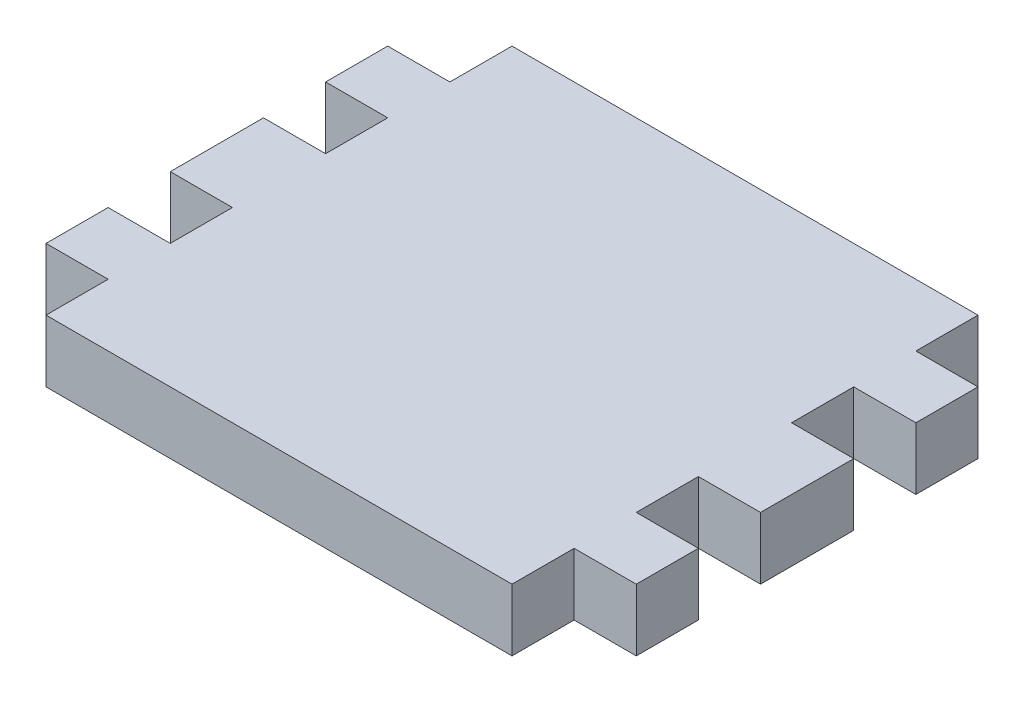
SolidWorks part; units mm, degrees
ref_plane "Front Plane" through (0, 0, 0) normal (0, 0, 1) x (1, 0, 0)
ref_plane "Top Plane" through (0, 0, 0) normal (0, 1, 0) x (1, 0, 0)
ref_plane "Right Plane" through (0, 0, 0) normal (1, 0, 0) x (0, 0, -1)
sketch "Sketch1" plane through (0, 0, 0) normal (0, 1, 0) x (1, 0, 0)
  line L1 (-17.8026, 11.0462) -> (30.4574, 11.0462)
  line L2 (-17.8026, 11.0462) -> (-17.8026, -27.0538)
  line L3 (-17.8026, -27.0538) -> (30.4574, -27.0538)
  line L4 (30.4574, 11.0462) -> (30.4574, -27.0538)
  dimension "D1" = 48.26
  dimension "D2" = 38.1
extrude "Boss-Extrude1" add sketch "Sketch1" along normal blind 5.08
sketch "Sketch2" plane through (0, 5.08, 0) normal (0, 1, 0) x (1, 0, 0)
  line L0 (25.3774, -27.0538) -> (25.3774, -21.9738)
  line L1 (-12.7226, 11.0462) -> (-12.7226, -27.0538) construction
  line L2 (30.4574, 11.0462) -> (-17.8026, 11.0462) construction
  line L3 (-17.8026, -27.0538) -> (30.4574, -27.0538) construction
  line L4 (6.3274, 11.0462) -> (6.3274, -27.0538) construction
  line L5 (-17.8026, 11.0462) -> (-17.8026, -27.0538) construction
  line L6 (25.3774, -16.8938) -> (25.3774, -11.8138)
  line L7 (-17.8026, 11.0462) -> (-12.7226, 11.0462)
  line L8 (-17.8026, 11.0462) -> (-17.8026, 5.9662)
  line L9 (-17.8026, 5.9662) -> (-12.7226, 5.9662)
  line L10 (-12.7226, 11.0462) -> (-12.7226, 5.9662)
  line L11 (-17.8026, 0.8862) -> (-12.7226, 0.8862)
  line L12 (-17.8026, 0.8862) -> (-17.8026, -4.1938)
  line L13 (-17.8026, -4.1938) -> (-12.7226, -4.1938)
  line L14 (-12.7226, 0.8862) -> (-12.7226, -4.1938)
  line L15 (-17.8026, -27.0538) -> (-12.7226, -27.0538)
  line L16 (-17.8026, -27.0538) -> (-17.8026, -21.9738)
  line L17 (-17.8026, -21.9738) -> (-12.7226, -21.9738)
  line L18 (-12.7226, -27.0538) -> (-12.7226, -21.9738)
  line L19 (-17.8026, -16.8938) -> (-12.7226, -16.8938)
  line L20 (-17.8026, -16.8938) -> (-17.8026, -11.8138)
  line L21 (-17.8026, -11.8138) -> (-12.7226, -11.8138)
  line L22 (-12.7226, -16.8938) -> (-12.7226, -11.8138)
  line L23 (25.3774, 0.8862) -> (25.3774, -4.1938)
  line L24 (25.3774, 11.0462) -> (25.3774, 5.9662)
  line L25 (30.4574, -11.8138) -> (25.3774, -11.8138)
  line L26 (30.4574, -16.8938) -> (30.4574, -11.8138)
  line L27 (30.4574, -16.8938) -> (25.3774, -16.8938)
  line L28 (30.4574, -21.9738) -> (25.3774, -21.9738)
  line L29 (30.4574, -27.0538) -> (30.4574, -21.9738)
  line L30 (30.4574, -27.0538) -> (25.3774, -27.0538)
  line L31 (30.4574, -4.1938) -> (25.3774, -4.1938)
  line L32 (30.4574, 0.8862) -> (30.4574, -4.1938)
  line L33 (30.4574, 0.8862) -> (25.3774, 0.8862)
  line L34 (30.4574, 5.9662) -> (25.3774, 5.9662)
  line L35 (30.4574, 11.0462) -> (30.4574, 5.9662)
  line L36 (30.4574, 11.0462) -> (25.3774, 11.0462)
  dimension "D1" = 5.08
  dimension "D2" = 5.08
  dimension "D3" = 5.08
  dimension "D4" = 5.08
  dimension "D5" = 5.08
  dimension "D6" = 5.08
  dimension "D7" = 5.08
extrude "Cut-Extrude1" cut sketch "Sketch2" against normal blind 5.08
